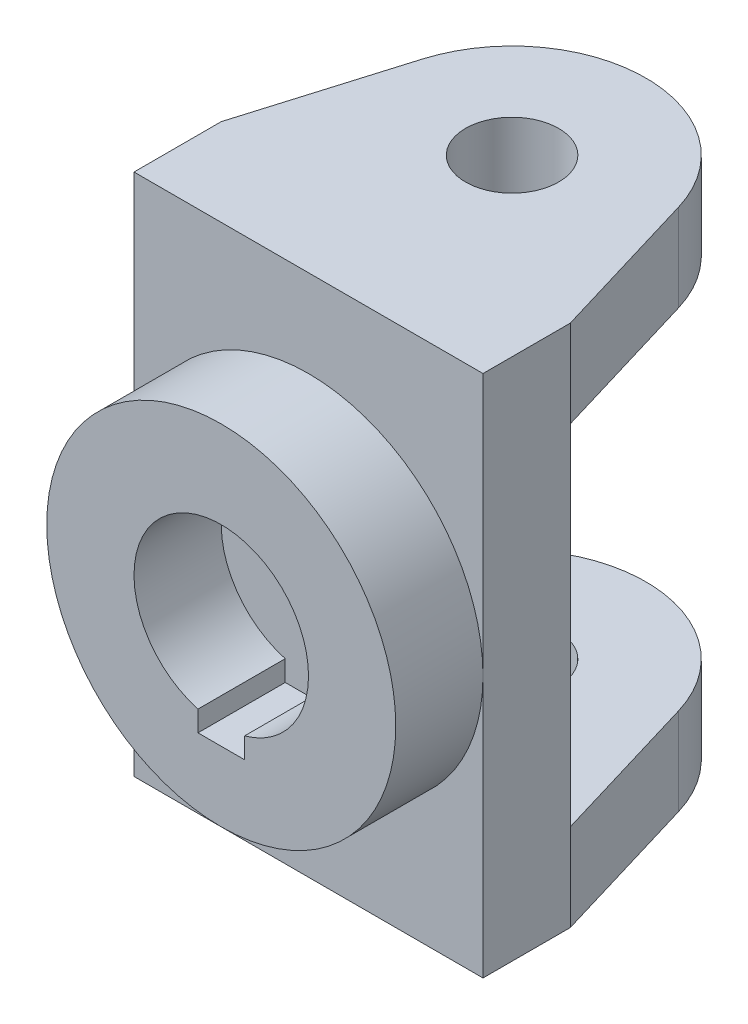
SolidWorks part; units mm, degrees
ref_plane "Front Plane" through (0, 0, 0) normal (0, 0, 1) x (1, 0, 0)
ref_plane "Top Plane" through (0, 0, 0) normal (0, 1, 0) x (1, 0, 0)
ref_plane "Right Plane" through (0, 0, 0) normal (1, 0, 0) x (0, 0, -1)
sketch "Sketch1" plane through (0, 0, 0) normal (0, 0, 1) x (1, 0, 0)
  line L1 (30, -45) -> (-30, -45)
  line L2 (30, -45) -> (30, 45)
  line L3 (30, 45) -> (-30, 45)
  line L4 (-30, -45) -> (-30, 45)
  line L5 (30, -45) -> (-30, 45) construction
  line L6 (30, 45) -> (-30, -45) construction
  point P0 (0, 0)
  dimension "D1" = 60
  dimension "D2" = 90
extrude "Boss-Extrude1" add sketch "Sketch1" along normal blind 15
sketch "Sketch2" plane through (0, 0, 15) normal (0, 0, 1) x (1, 0, 0)
  line L0 (-4, -14.4568) -> (-4, -18)
  line L3 (-4, -18) -> (4, -18)
  line L4 (4, -14.4568) -> (4, -18)
  arc A0 (4, -14.4568) -> (-4, -14.4568) centre (0, 0) ccw
  circle A1 centre (0, 0) radius 30
  dimension "D1" = 30
  dimension "D2" = 60
extrude "Boss-Extrude2" add sketch "Sketch2" along normal blind 15
sketch "Sketch3" plane through (0, 45, 0) normal (0, 1, 0) x (1, 0, 0)
  line L0 (-30, -15) -> (30, -15) construction
  line L1 (30, 0) -> (22.0329, 26.5993)
  line L2 (-30, 0) -> (-22.0329, 26.5993)
  line L3 (-30, 0) -> (30, 0)
  circle A0 centre (0, 20) radius 8
  arc A1 (22.0329, 26.5993) -> (-22.0329, 26.5993) centre (0, 20) ccw
  dimension "D1" = 46
  dimension "D2" = 16
  dimension "D3" = 35
extrude "Boss-Extrude3" add sketch "Sketch3" against normal blind 15
mirror "Mirror1" about plane through (0, 0, 0) normal (0, 1, 0) of "Boss-Extrude3"
